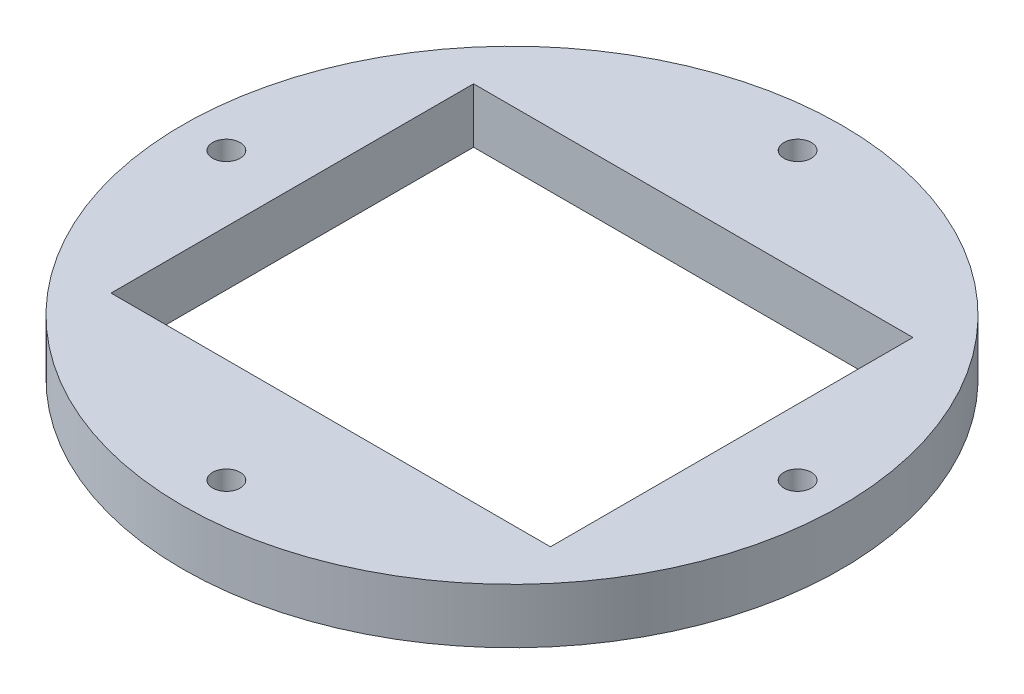
SolidWorks part; units mm, degrees
ref_plane "Front Plane" through (0, 0, 0) normal (0, 0, 1) x (1, 0, 0)
ref_plane "Top Plane" through (0, 0, 0) normal (0, 1, 0) x (1, 0, 0)
ref_plane "Right Plane" through (0, 0, 0) normal (1, 0, 0) x (0, 0, -1)
sketch "Sketch1" plane through (0, 0, 0) normal (0, 1, 0) x (1, 0, 0)
  line L1 (-25.4, -20.955) -> (25.4, -20.955)
  line L2 (-25.4, -20.955) -> (-25.4, 20.955)
  line L3 (-25.4, 20.955) -> (25.4, 20.955)
  line L4 (25.4, -20.955) -> (25.4, 20.955)
  line L5 (-25.4, -20.955) -> (25.4, 20.955) construction
  line L6 (-25.4, 20.955) -> (25.4, -20.955) construction
  circle A0 centre (0, 0) radius 38.1
  circle A1 centre (0, 33.02) radius 1.5875
  circle A2 centre (33.02, 0) radius 1.5875
  circle A3 centre (0, -33.02) radius 1.5875
  circle A4 centre (-33.02, 0) radius 1.5875
  point P14 (0, 0)
  dimension "D1" = 76.2
  dimension "D3" = 3.175
  dimension "D4" = 33.02
  dimension "D5" = 41.91
  dimension "D6" = 50.8
  dimension "D2" = 4
extrude "Boss-Extrude1" add sketch "Sketch1" along normal blind 6.35
